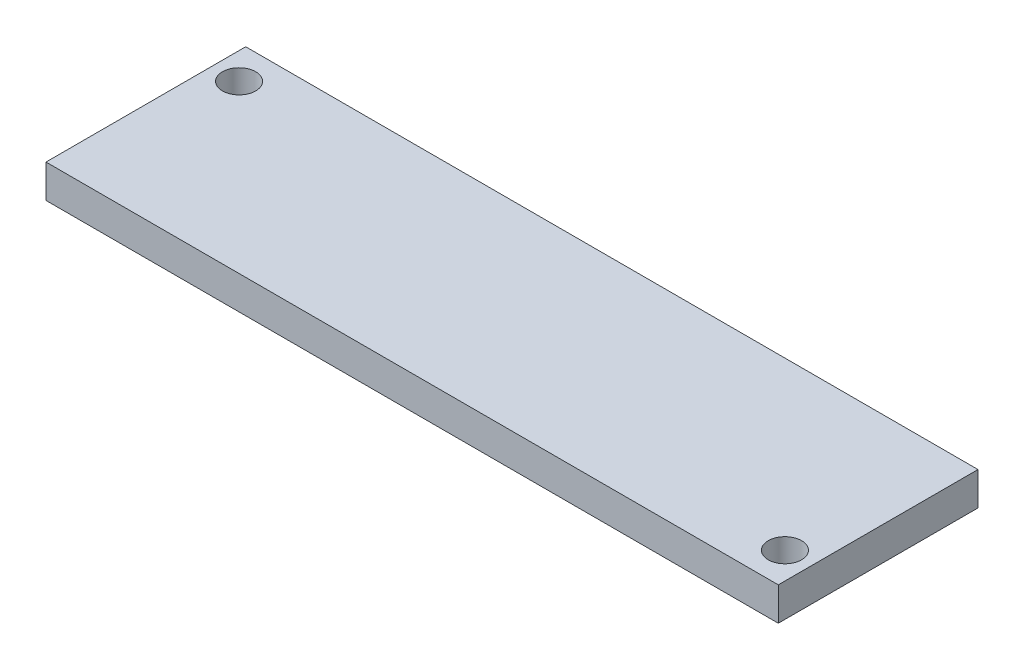
SolidWorks part; units mm, degrees
ref_plane "Ebene vorne" through (0, 0, 0) normal (0, 0, 1) x (1, 0, 0)
ref_plane "Ebene oben" through (0, 0, 0) normal (0, 1, 0) x (1, 0, 0)
ref_plane "Ebene rechts" through (0, 0, 0) normal (1, 0, 0) x (0, 0, -1)
sketch "Skizze1" plane through (0, 0, 0) normal (0, 1, 0) x (1, 0, 0)
  line L0 (-55, 0) -> (55, 0) construction
  line L1 (-55, -15) -> (55, -15)
  line L2 (-55, -15) -> (-55, 15)
  line L3 (-55, 15) -> (55, 15)
  line L4 (55, -15) -> (55, 15)
  line L5 (-55, -15) -> (55, 15) construction
  line L6 (-55, 15) -> (55, -15) construction
  line L7 (0, 0) -> (0, -15) construction
  circle A0 centre (-51, 10) radius 2.5
  circle A1 centre (-51, -10) radius 2.5 construction
  circle A2 centre (51, -10) radius 2.5
  point P0 (0, 0)
  dimension "D3" = 5
  dimension "D1" = 110
  dimension "D2" = 30
  dimension "D4" = 4
  dimension "D5" = 5
extrude "Aufsatz-Linear austragen1" add sketch "Skizze1" along normal blind 5
